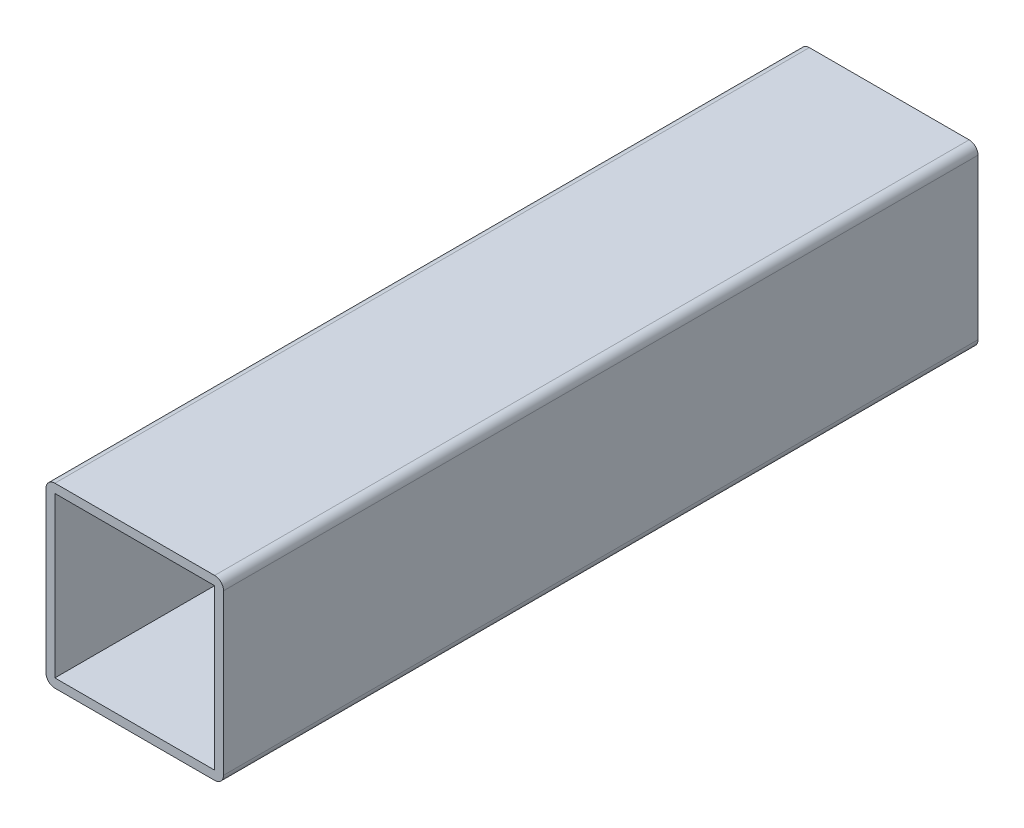
SolidWorks part; units mm, degrees
material "1.4305 (X8CrNiS18-9)"
ref_plane "Ön Düzlem" through (0, 0, 0) normal (0, 0, 1) x (1, 0, 0)
ref_plane "Üst Düzlem" through (0, 0, 0) normal (0, 1, 0) x (1, 0, 0)
ref_plane "Sağ Düzlem" through (0, 0, 0) normal (1, 0, 0) x (0, 0, -1)
sketch "Çizim1" plane through (0, 0, 0) normal (0, 0, 1) x (1, 0, 0)
  line L0 (-36, 36) -> (-36, -36)
  line L1 (-36, 40) -> (36, 40)
  line L2 (-40, 36) -> (-40, -36)
  line L3 (-36, -40) -> (36, -40)
  line L4 (40, 36) -> (40, -36)
  line L5 (-40, 40) -> (40, -40) construction
  line L6 (-40, -40) -> (40, 40) construction
  line L7 (-36, -36) -> (36, -36)
  line L8 (36, 36) -> (36, -36)
  line L9 (-36, 36) -> (36, 36)
  arc A0 (40, -36) -> (36, -40) centre (36, -36) cw
  arc A1 (36, 40) -> (40, 36) centre (36, 36) cw
  arc A2 (-36, 40) -> (-40, 36) centre (-36, 36) ccw
  arc A3 (-40, -36) -> (-36, -40) centre (-36, -36) ccw
  arc A4 (-36, -36) -> (-36, -36) centre (-36, -36) ccw
  arc A5 (36, -36) -> (36, -36) centre (36, -36) cw
  arc A6 (36, 36) -> (36, 36) centre (36, 36) cw
  arc A7 (-36, 36) -> (-36, 36) centre (-36, 36) ccw
  point P0 (0, 0)
  dimension "D3" = 4
  dimension "D1" = 80
  dimension "D2" = 80
  dimension "D4" = 4
extrude "Yükseklik-Ekstrüzyon1" add sketch "Çizim1" along normal blind 340
